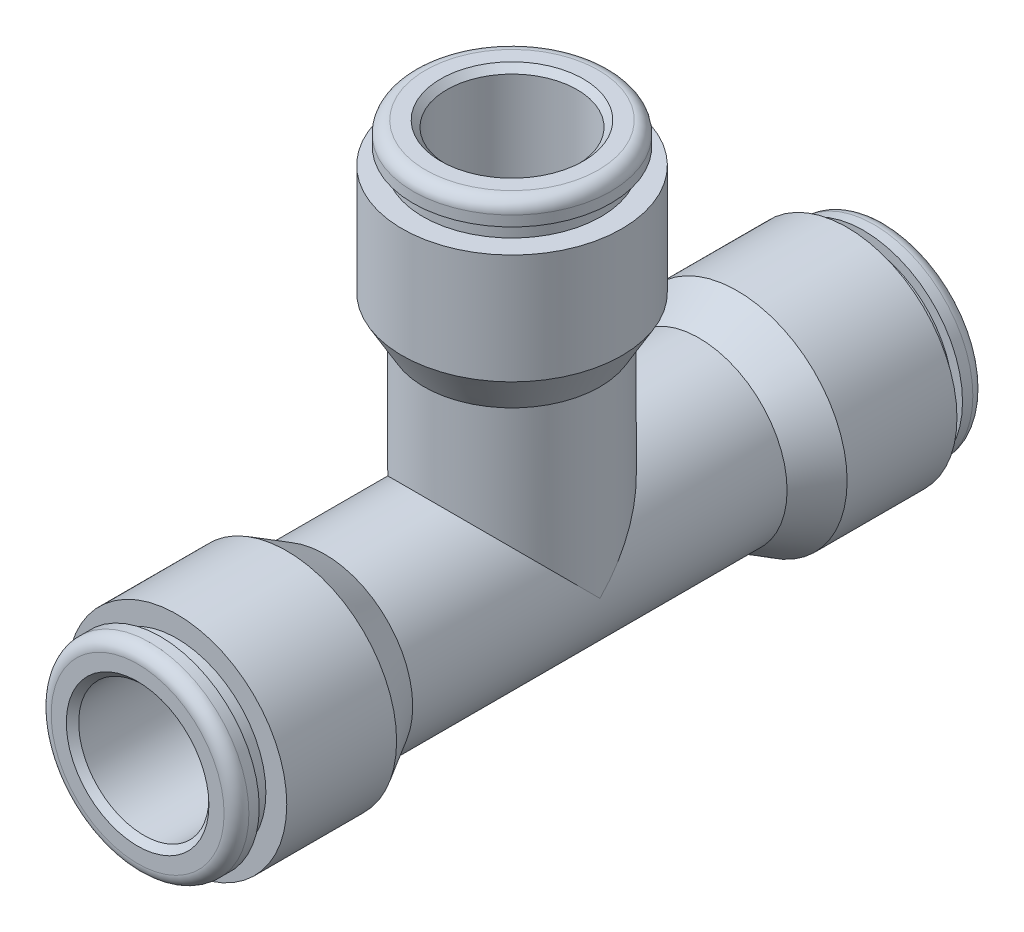
SolidWorks part; units mm, degrees
ref_plane "Front Plane" through (0, 0, 0) normal (0, 0, 1) x (1, 0, 0)
ref_plane "Top Plane" through (0, 0, 0) normal (0, 1, 0) x (1, 0, 0)
ref_plane "Right Plane" through (0, 0, 0) normal (1, 0, 0) x (0, 0, -1)
sketch "Sketch1" plane through (0, 0, 0) normal (1, 0, 0) x (0, 0, -1)
  line L0 (21.603, 6.075) -> (22.238, 6.075)
  line L1 (13.8383, 6.75) -> (20.587, 6.75)
  line L2 (0, 5.4) -> (0, 3.238)
  line L3 (6.9, 4) -> (22.619, 4)
  line L4 (23, 5.313) -> (23, 4.381)
  line L5 (0, 0) -> (0, 22.75) construction
  line L6 (20.587, 6.75) -> (20.587, 5.4675)
  line L7 (20.587, 5.4675) -> (21.603, 5.4675)
  line L8 (21.603, 6.075) -> (21.603, 5.4675)
  line L9 (-6.75, 22.75) -> (6.75, 22.75) construction
  line L10 (0, 0) -> (23, 0) construction
  line L11 (6.9, 4) -> (6.9, 3.238)
  line L12 (22.619, 4) -> (23, 4.381)
  line L13 (0, 0) -> (0, 3.238) construction
  line L14 (0, 5.4) -> (11.5, 5.4)
  line L15 (11.5, 5.4) -> (13.8383, 6.75)
  line L16 (6.9, 3.238) -> (0, 3.238)
  line L17 (0, 23) -> (0, 0) construction
  line L22 (0, 0) -> (-23, 0) construction
  arc A0 (22.238, 6.075) -> (23, 5.313) centre (22.238, 5.313) cw
  point P1 (23, 4)
  point P2 (23, 6.75)
  point P17 (23, -6.75)
  point P20 (23, 6.075)
  point P26 (-23, -6.75)
  dimension "D4" = 0.762
  dimension "tube od" = 8
  dimension "D1" = 1.397
  dimension "D2" = 1.016
  dimension "D3" = 10.935
  dimension "D6" = 12.15
  dimension "D9" = 30
  dimension "D10" = 10.8
  dimension "D5" = 11.5
  dimension "D8" = 13.5
  dimension "D11" = 0.762
revolve "Revolve1" add sketch "Sketch1" angle 360 about L10
ref_axis "Axis1" through (-6.05, 0, 0) along (1, 0, 0)
pattern_circular "CirPattern1" count 3 over 180 about axis through (0, 0, 0) along (1, 0, 0) of bodies 118 123
move or copy body "Body-Move/Copy1" bodies to move or copy 124 copy no translate (0, -0.25, 0)
sketch "Sketch3" plane through (0, 0, 0) normal (0, 1, 0) x (1, 0, 0)
  circle A0 centre (0, 0) radius 5.4 construction
  circle A1 centre (0, 0) radius 5.4
extrude "Cut-Extrude2" cut sketch "Sketch3" against normal through all and the other way blind 0.1 draft 45
sketch "Sketch4" plane through (0, 0, 0) normal (1, 0, 0) x (0, 0, -1)
  line L0 (4, 22.369) -> (4.381, 22.75)
  line L1 (4.381, 22.75) -> (0, 22.75)
  line L2 (0, 22.75) -> (0, 0)
  line L4 (3.238, 0) -> (3.238, 6.65)
  line L5 (3.238, 6.65) -> (4, 6.65)
  line L6 (4, 6.65) -> (4, 22.369)
  line L7 (3.238, 0) -> (0, 0)
  line L9 (3.238, 6.65) -> (-3.238, 6.65) construction
  line L10 (4, 6.65) -> (-4, 6.65) construction
revolve "Cut-Revolve2" cut sketch "Sketch4" angle 360 about L5
combine bodies "Combine1" operation type add bodies to combine 145 144 146
sketch "Sketch5" plane through (0, 0, 0) normal (1, 0, 0) x (0, 0, -1)
  line L0 (23, 4.381) -> (22.619, 4)
  line L1 (22.619, 4) -> (6.9, 4)
  line L2 (6.9, 4) -> (6.9, 3.238)
  line L3 (6.9, 3.238) -> (0, 3.238)
  line L4 (0, 3.238) -> (0, 0)
  line L5 (0, 0) -> (23, 0)
  line L6 (23, 0) -> (23, 4.381)
revolve "Cut-Revolve1" cut sketch "Sketch5" angle 360 about L5
pattern_circular "CirPattern2" count 2 over 180 about axis through (-6.05, 0, 0) along (1, 0, 0) of "Cut-Revolve1"
equation "\"D6@Sketch1\" = \"G@Sketch1\"*.9"
equation "\"D3@Sketch1\" = \"D6@Sketch1\"*.9"
equation "\"D10@Sketch1\" = \"G@Sketch1\"*.8"
equation "\"D5@Sketch1\" = \"L/2@Sketch1\"*.5"
equation "\"D8@Sketch1\" = \"G@Sketch1\""
